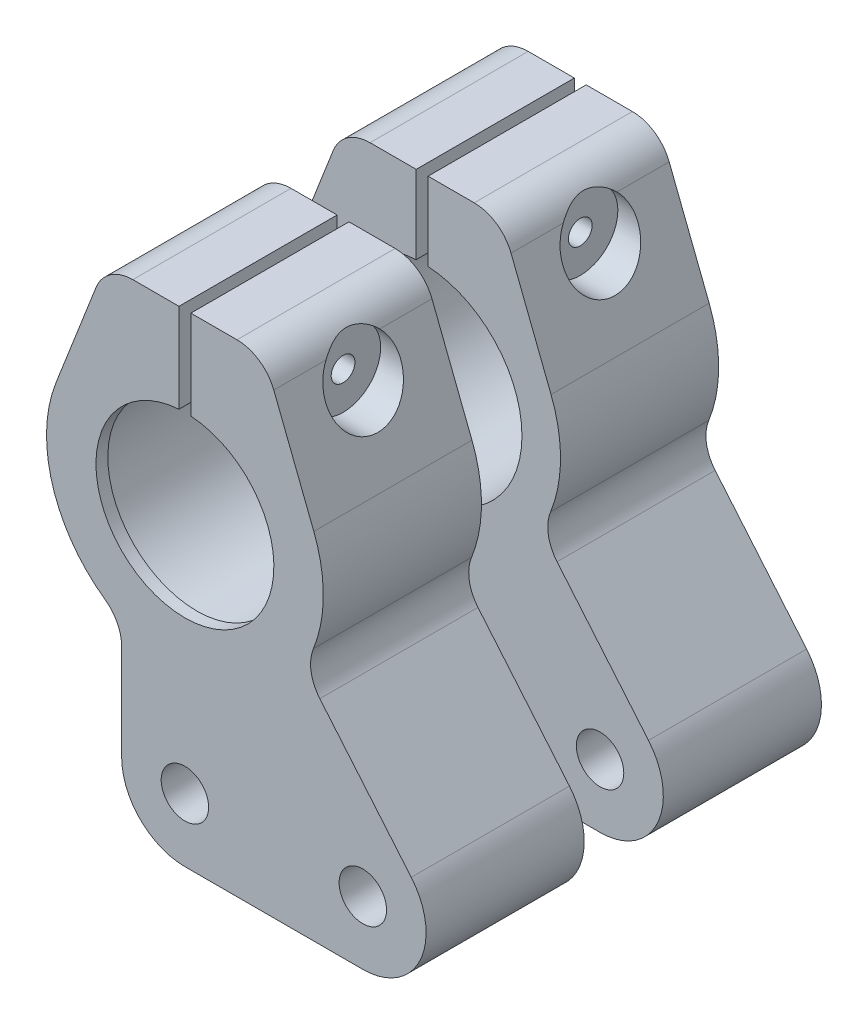
SolidWorks part; units mm, degrees
ref_plane "Front Plane" through (0, 0, 0) normal (0, 0, 1) x (1, 0, 0)
ref_plane "Top Plane" through (0, 0, 0) normal (0, 1, 0) x (1, 0, 0)
ref_plane "Right Plane" through (0, 0, 0) normal (1, 0, 0) x (0, 0, -1)
sketch "Sketch1" plane through (0, 0, 0) normal (0, 0, 1) x (1, 0, 0)
  line L0 (-16, -61) -> (-16, -31.1288)
  line L1 (-35, 0) -> (-35, -61) construction
  line L2 (-35, 0) -> (35, 0) construction
  line L3 (35, 0) -> (35, -61) construction
  line L4 (-35, -61) -> (35, -61) construction
  line L5 (-118.031, -40) -> (118.031, -40) construction
  line L6 (16, -61) -> (16, -31.1288)
  line L7 (57.2567, -50.7154) -> (29.9283, -18.1466)
  line L8 (0, -77) -> (45, -77)
  line L9 (-32.6019, 12.7325) -> (-20, 45)
  line L10 (-20, 45) -> (20, 45)
  line L11 (32.6019, 12.7325) -> (20, 45)
  line L12 (0, 0) -> (0, 72.2071) construction
  line L13 (-93.7303, 35) -> (93.7303, 35) construction
  line L14 (-1.5, 45) -> (-1.5, 25.2054)
  line L15 (1.5, 45) -> (1.5, 25.2054)
  circle A0 centre (0, 0) radius 25.25
  circle A1 centre (0, -61) radius 6
  circle A2 centre (0, 0) radius 35
  circle A3 centre (0, -61) radius 16
  circle A4 centre (0, 0) radius 40 construction
  circle A5 centre (45, -61) radius 6
  circle A6 centre (45, -61) radius 16
  point P20 (0, -40)
  point P28 (0, 45)
  point P34 (0, 35)
  dimension "D1" = 50.5
  dimension "D2" = 12
  dimension "D4" = 70
  dimension "D5" = 32
  dimension "D6" = 35
  dimension "D7" = 80
  dimension "D9" = 32
  dimension "D8" = 12
  dimension "D3" = 61
  dimension "D10" = 45
  dimension "D11" = 50
  dimension "D12" = 40
  dimension "D13" = 45
  dimension "D14" = 1.5
extrude "Boss-Extrude3" add sketch "Sketch1" along normal blind 40 contours A2 L14 L10 L9 | A2 L11 L10 L15 | A2 L15 A0 L14 | A6 L7 A2 L6 A3 L8 | A3 L6 A2 L0 | A3 A1 | A6 A5
fillet "Fillet2" radius 10 4 edges at (-16, -31.1288, 20) (29.9283, -18.1466, 20) (-20, 45, 20) (20, 45, 20)
ref_plane "Plane1" through (-20, 0, 0) normal (1, 0, 0) x (0, 0, -1)
sketch "Sketch5" plane through (-20, 0, 0) normal (1, 0, 0) x (0, 0, -1)
  line L0 (0, 45) -> (-40, 45) construction
  line L1 (-40, 12.7325) -> (-40, 38.6379) construction
  circle A0 centre (-20, 32) radius 9.5
  dimension "D3" = 19
  dimension "D1" = 13
  dimension "D2" = 20
extrude "Cut-Extrude1" cut sketch "Sketch5" against normal blind 10
sketch "Sketch6" plane through (-20, 0, 0) normal (-1, 0, 0) x (0, 0, 1)
  circle A0 centre (20, 32) radius 3
  dimension "D1" = 6
extrude "Cut-Extrude2" cut sketch "Sketch6" against normal up to surface (21.5 mm away)
mirror "Mirror3" about plane through (0, 0, 0) normal (1, 0, 0) of "Cut-Extrude2", "Cut-Extrude1"
sketch "Sketch7" plane through (0, 0, 40) normal (0, 0, 1) x (1, 0, 0)
  line L0 (0, 0) -> (0, 36.4439) construction
  line L1 (-1.5, 22.4499) -> (-1.5, 25.2054)
  line L2 (1.5, 22.4499) -> (1.5, 25.2054)
  circle A0 centre (0, 0) radius 22.5
  circle A1 centre (0, 0) radius 25.25
  arc M17 (1.5, 25.2054) -> (-1.5, 25.2054) centre (0, 0) cw
  dimension "D1" = 45
  dimension "D2" = 50.5
extrude "Boss-Extrude4" add sketch "Sketch7" against normal blind 3 contours A0 L1 L2 M17
ref_plane "Plane3" through (0, 0, -10) normal (0, 0, 1) x (1, 0, 0)
mirror "Mirror6" about plane through (0, 0, -10) normal (0, 0, 1) of bodies 109
